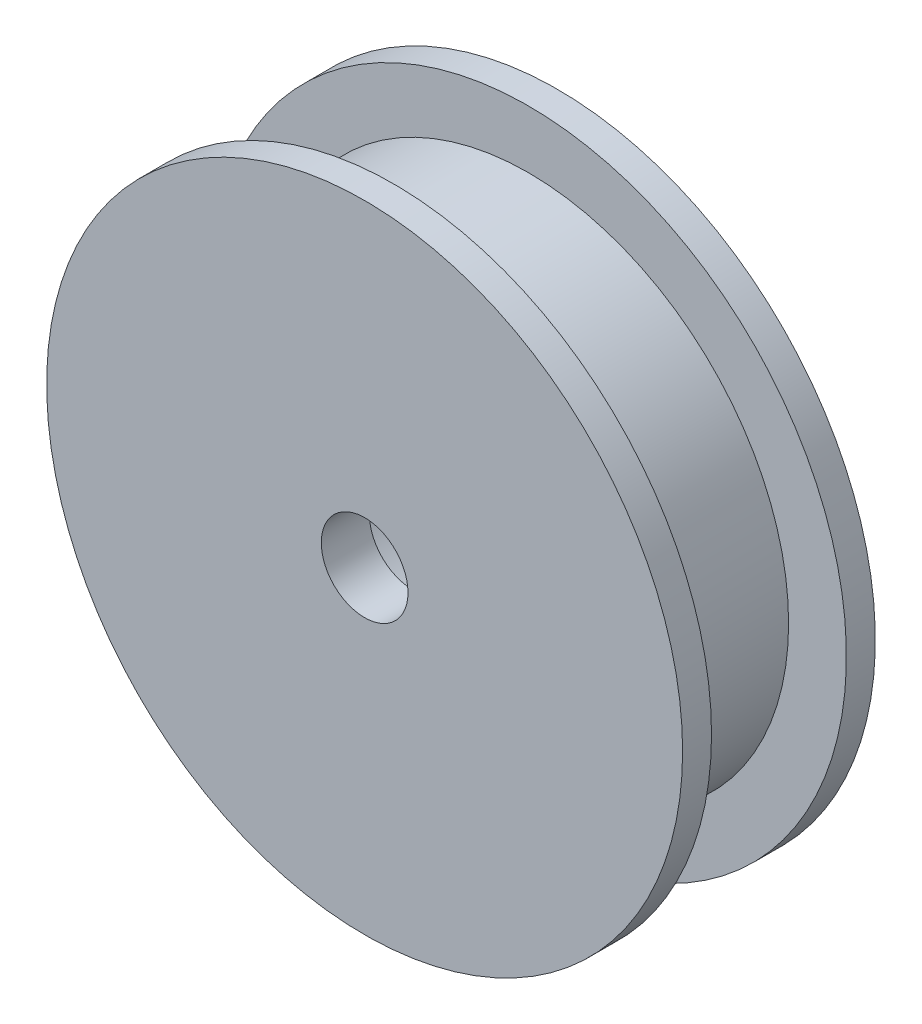
SolidWorks part; units mm, degrees
ref_plane "Front Plane" through (0, 0, 0) normal (0, 0, 1) x (1, 0, 0)
ref_plane "Top Plane" through (0, 0, 0) normal (0, 1, 0) x (1, 0, 0)
ref_plane "Right Plane" through (0, 0, 0) normal (1, 0, 0) x (0, 0, -1)
sketch "Sketch1" plane through (0, 0, 0) normal (0, 0, 1) x (1, 0, 0)
  circle A0 centre (0, 0) radius 13.5
  dimension "D1" = 27
extrude "Boss-Extrude1" add sketch "Sketch1" along normal blind 7
sketch "Sketch2" plane through (0, 0, 7) normal (0, 0, 1) x (1, 0, 0)
  circle A0 centre (0, 0) radius 16.5
  circle A1 centre (0, 0) radius 13.5 construction
  dimension "D1" = 3
extrude "Boss-Extrude2" add sketch "Sketch2" along normal blind 1.5
sketch "Sketch3" plane through (0, 0, 0) normal (0, 0, -1) x (-1, 0, 0)
  circle A0 centre (0, 0) radius 16.5
  circle A2 centre (0, 0) radius 16.5 construction
extrude "Boss-Extrude3" add sketch "Sketch3" along normal blind 1.5
sketch "Sketch4" plane through (0, 0, 8.5) normal (0, 0, 1) x (1, 0, 0)
  circle A0 centre (0, 0) radius 6.5
  dimension "D1" = 13
extrude "Cut-Extrude1" cut sketch "Sketch4" against normal through all
sketch "Sketch5" plane through (0, 0, 8.5) normal (0, 0, 1) x (1, 0, 0)
  circle A0 centre (0, 0) radius 6.5
  circle A1 centre (0, 0) radius 2.25
  dimension "D1" = 4.5
extrude "Boss-Extrude4" add sketch "Sketch5" against normal blind 2.5
